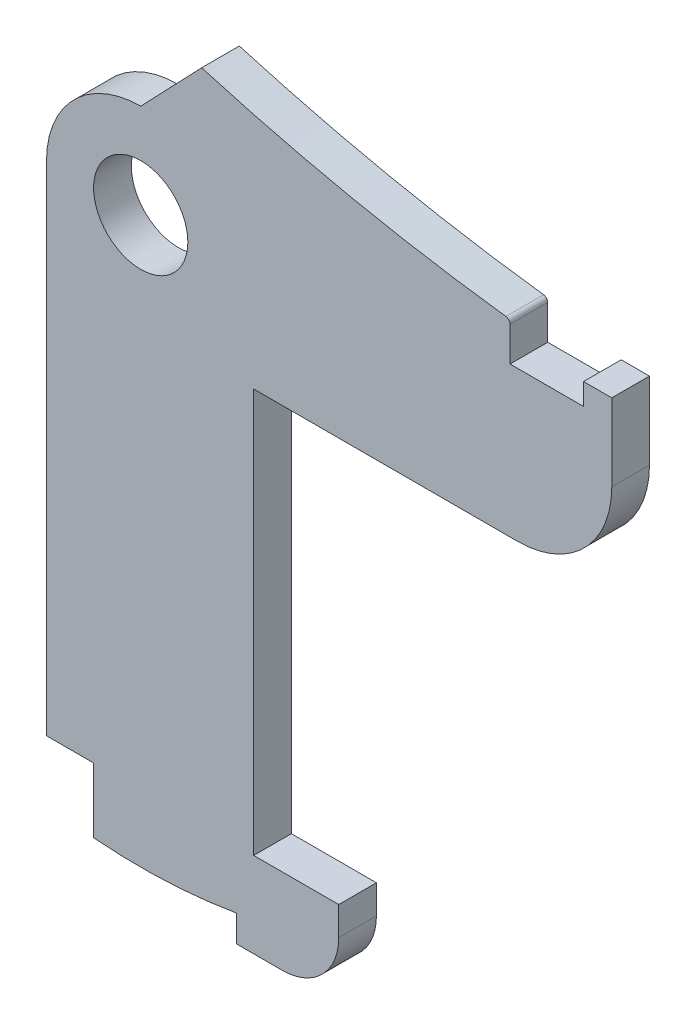
SolidWorks part; units mm, degrees
ref_plane "정면" through (0, 0, 0) normal (0, 0, 1) x (1, 0, 0)
ref_plane "윗면" through (0, 0, 0) normal (0, 1, 0) x (1, 0, 0)
ref_plane "우측면" through (0, 0, 0) normal (1, 0, 0) x (0, 0, -1)
sketch "스케치1" plane through (0, 0, 0) normal (0, 0, 1) x (1, 0, 0)
  line L1 (17.6552, -8.2873) -> (20.8871, -4.904)
  line L15 (37.2552, -8.5081) -> (37.2552, -10.3366)
  line L16 (37.2552, -10.3366) -> (41.1552, -10.3366)
  line L20 (41.1552, -10.3366) -> (41.1552, -9.1914)
  line L21 (41.1552, -9.1914) -> (42.6552, -9.1914)
  line L22 (42.6552, -9.1914) -> (42.6552, -13.2873)
  line L23 (37.6552, -18.2873) -> (23.65, -18.2873)
  line L24 (23.65, -18.2873) -> (23.65, -39.725)
  line L25 (22.7313, -44.2491) -> (25.1634, -44.2491)
  line L26 (12.6552, -39.725) -> (12.6552, -13.2873)
  line L27 (28.1634, -41.2491) -> (28.1634, -39.725)
  line L28 (28.1634, -39.725) -> (23.65, -39.725)
  line L29 (23.65, -39.725) -> (25.9067, -39.725)
  line L33 (15.1552, -43.1618) -> (15.1552, -39.725)
  line L34 (15.1552, -39.725) -> (12.6552, -39.725)
  line L35 (22.7313, -42.8333) -> (22.7313, -44.2491)
  arc A0 (37.0363, -8.2601) -> (37.2552, -8.5081) centre (37.0052, -8.5081) cw
  arc A1 (25.1634, -44.2491) -> (28.1634, -41.2491) centre (25.1634, -41.2491) ccw
  circle A3 centre (17.6552, -13.2873) radius 2.5
  arc A6 (17.6552, -8.2873) -> (12.6552, -13.2873) centre (17.6552, -13.2873) ccw
  arc A7 (15.1552, -43.1618) -> (22.7313, -42.8333) centre (17.6552, -13.2873) ccw
  arc A9 (37.0363, -8.2601) -> (20.8871, -4.904) centre (49.9016, 94.181) cw
  arc A10 (42.6552, -13.2873) -> (37.6552, -18.2873) centre (37.6552, -13.2873) cw
  point P4 (37.2552, -8.2873)
  dimension "D1" = 19.6
  dimension "D2" = 1.5
  dimension "D3" = 103.2458
  dimension "D5" = 5
  dimension "D6" = 5
  dimension "D4" = 0.25
  dimension "D8" = 3
  dimension "D7" = 30
extrude "보스-돌출1" add sketch "스케치1" along normal blind 2
